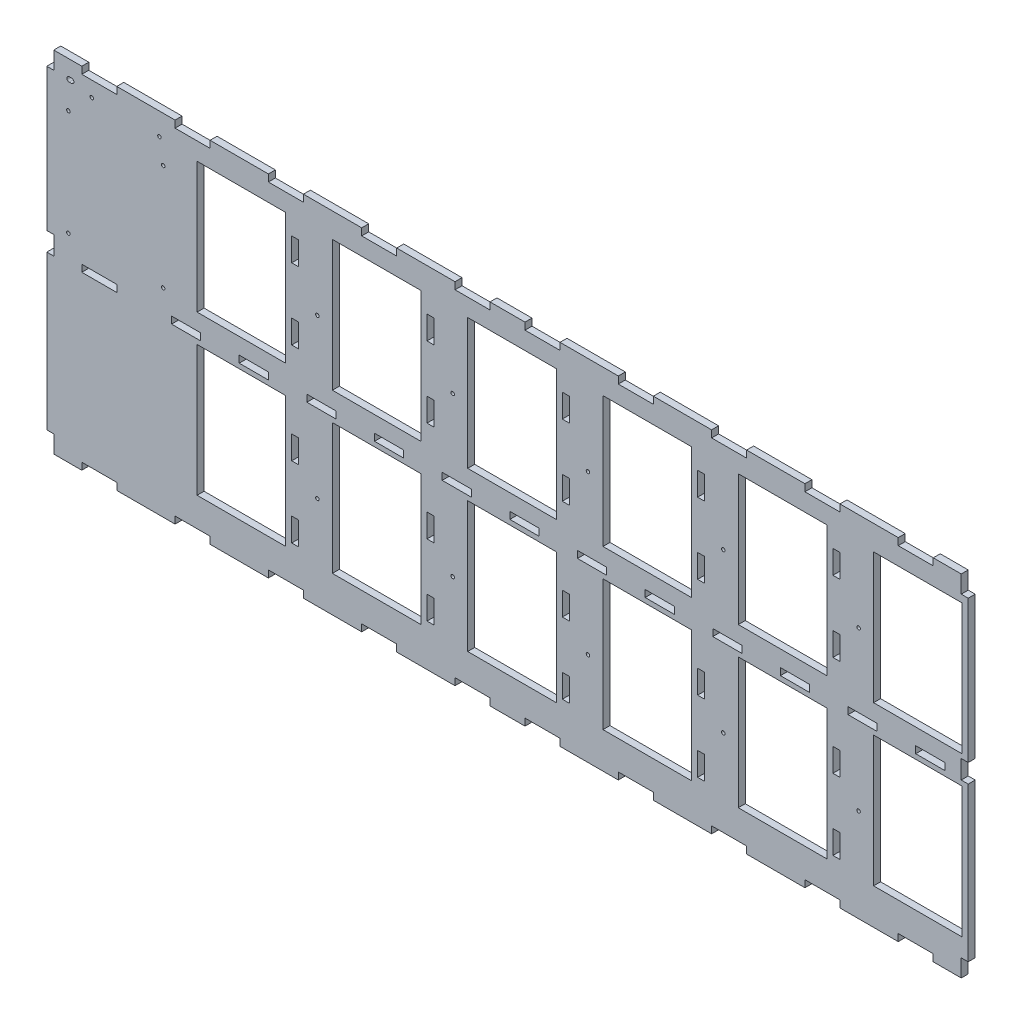
SolidWorks part; units mm, degrees
material "Acrylic (Medium-high impact)"
ref_plane "Front Plane" through (0, 0, 0) normal (0, 0, 1) x (1, 0, 0)
ref_plane "Top Plane" through (0, 0, 0) normal (0, 1, 0) x (1, 0, 0)
ref_plane "Right Plane" through (0, 0, 0) normal (1, 0, 0) x (0, 0, -1)
sketch "Sketch1" plane through (0, 0, 0) normal (0, 0, 1) x (1, 0, 0)
  line L1 (395, -150) -> (-395, -150)
  line L2 (395, -150) -> (395, 150)
  line L3 (395, 150) -> (-395, 150)
  line L4 (-395, -150) -> (-395, 150)
  line L5 (395, -150) -> (-395, 150) construction
  line L6 (395, 150) -> (-395, -150) construction
  line L7 (-266.15, 16.85) -> (-190.15, 16.85)
  line L8 (-266.15, 16.85) -> (-266.15, 128.85)
  line L9 (-266.15, 128.85) -> (-190.15, 128.85)
  line L10 (-190.15, 16.85) -> (-190.15, 128.85)
  line L11 (-264.15, 18.85) -> (-264.15, 126.85) construction
  line L12 (-192.15, 18.85) -> (-264.15, 18.85) construction
  line L13 (-192.15, 126.85) -> (-192.15, 18.85) construction
  line L14 (-264.15, 126.85) -> (-192.15, 126.85) construction
  line L15 (-150.15, 16.85) -> (-74.15, 16.85)
  line L16 (-150.15, 16.85) -> (-150.15, 128.85)
  line L17 (-150.15, 128.85) -> (-74.15, 128.85)
  line L18 (-74.15, 16.85) -> (-74.15, 128.85)
  line L19 (-34.15, 16.85) -> (41.85, 16.85)
  line L20 (-34.15, 16.85) -> (-34.15, 128.85)
  line L21 (-34.15, 128.85) -> (41.85, 128.85)
  line L22 (41.85, 16.85) -> (41.85, 128.85)
  line L23 (81.85, 16.85) -> (157.85, 16.85)
  line L24 (81.85, 16.85) -> (81.85, 128.85)
  line L25 (81.85, 128.85) -> (157.85, 128.85)
  line L26 (157.85, 16.85) -> (157.85, 128.85)
  line L27 (197.85, 16.85) -> (273.85, 16.85)
  line L28 (197.85, 16.85) -> (197.85, 128.85)
  line L29 (197.85, 128.85) -> (273.85, 128.85)
  line L30 (273.85, 16.85) -> (273.85, 128.85)
  line L31 (-150.15, -119.15) -> (-74.15, -119.15)
  line L32 (-150.15, -119.15) -> (-150.15, -7.15)
  line L33 (-150.15, -7.15) -> (-74.15, -7.15)
  line L34 (-74.15, -119.15) -> (-74.15, -7.15)
  line L35 (-34.15, -119.15) -> (41.85, -119.15)
  line L36 (-34.15, -119.15) -> (-34.15, -7.15)
  line L37 (-34.15, -7.15) -> (41.85, -7.15)
  line L38 (41.85, -119.15) -> (41.85, -7.15)
  line L39 (81.85, -119.15) -> (157.85, -119.15)
  line L40 (81.85, -119.15) -> (81.85, -7.15)
  line L41 (81.85, -7.15) -> (157.85, -7.15)
  line L42 (157.85, -119.15) -> (157.85, -7.15)
  line L43 (197.85, -119.15) -> (273.85, -119.15)
  line L44 (197.85, -119.15) -> (197.85, -7.15)
  line L45 (197.85, -7.15) -> (273.85, -7.15)
  line L46 (273.85, -119.15) -> (273.85, -7.15)
  line L47 (-266.15, -119.15) -> (-190.15, -119.15)
  line L48 (-266.15, -119.15) -> (-266.15, -7.15)
  line L49 (-266.15, -7.15) -> (-190.15, -7.15)
  line L50 (-190.15, -119.15) -> (-190.15, -7.15)
  line L51 (313.85, 16.85) -> (389.85, 16.85)
  line L52 (313.85, 16.85) -> (313.85, 128.85)
  line L53 (313.85, 128.85) -> (389.85, 128.85)
  line L54 (389.85, 16.85) -> (389.85, 128.85)
  line L55 (313.85, -119.15) -> (389.85, -119.15)
  line L56 (313.85, -119.15) -> (313.85, -7.15)
  line L57 (313.85, -7.15) -> (389.85, -7.15)
  line L58 (389.85, -119.15) -> (389.85, -7.15)
  point P0 (0, 0)
  dimension "D1" = 790
  dimension "D2" = 300
  dimension "D3" = 2
  dimension "D4" = 2
  dimension "D5" = 2
  dimension "D6" = 2
  dimension "D7" = 6
  dimension "D8" = 2
extrude "Boss-Extrude1" add sketch "Sketch1" along normal blind 6
sketch "Sketch2" plane through (0, 0, 6) normal (0, 0, 1) x (1, 0, 0)
  line L0 (336, -70) -> (301, -70) construction
  line L1 (336, 66) -> (301, 66) construction
  circle A0 centre (301, -70) radius 1.5
  circle A1 centre (301, 66) radius 1.5
  circle A2 centre (185, -70) radius 1.5
  circle A3 centre (185, 66) radius 1.5
  circle A4 centre (69, -70) radius 1.5
  circle A5 centre (69, 66) radius 1.5
  circle A6 centre (-47, -70) radius 1.5
  circle A7 centre (-47, 66) radius 1.5
  circle A8 centre (-163, -70) radius 1.5
  circle A9 centre (-163, 66) radius 1.5
  circle A10 centre (-295.18, 20.3188) radius 1.5
  circle A11 centre (-376.46, 20.3188) radius 1.5
  circle A12 centre (-376.46, 111.1612) radius 1.5
  circle A13 centre (-295.18, 111.1612) radius 1.5
  circle A14 centre (-298.4147, 130.9983) radius 1.5
  circle A15 centre (-356.4147, 130.9983) radius 1.5
  dimension "D2" = 3
  dimension "D1" = 35
  dimension "D3" = 5
extrude "Cut-Extrude1" cut sketch "Sketch2" against normal blind 10
sketch "Sketch3" plane through (0, 0, 6) normal (0, 0, 1) x (1, 0, 0)
  line L0 (395, -150) -> (395, 150) construction
  line L1 (395, 135) -> (389, 135)
  line L2 (395, 135) -> (395, 150)
  line L3 (395, 150) -> (389, 150)
  line L4 (389, 135) -> (389, 150)
  line L5 (395, 150) -> (-395, 150) construction
  line L6 (389, 150) -> (389, 135) construction
  line L7 (395, -3) -> (389, -3)
  line L8 (395, -3) -> (395, 13)
  line L9 (395, 13) -> (389, 13)
  line L10 (389, -3) -> (389, 13)
  line L11 (-395, -150) -> (395, -150) construction
  line L12 (395, -135) -> (389, -135)
  line L13 (395, -135) -> (395, -150)
  line L14 (395, -150) -> (389, -150)
  line L15 (389, -135) -> (389, -150)
  line L16 (0, 50.7716) -> (0, 0) construction
  line L18 (0, 0) -> (100.6607, 0) construction
  line L19 (-389, -135) -> (-389, -150)
  line L20 (-395, -150) -> (-389, -150)
  line L21 (-395, -135) -> (-395, -150)
  line L22 (-395, -135) -> (-389, -135)
  line L23 (-389, -3) -> (-389, 13)
  line L24 (-395, 13) -> (-389, 13)
  line L25 (-395, -3) -> (-395, 13)
  line L26 (-395, -3) -> (-389, -3)
  line L27 (-389, 135) -> (-389, 150)
  line L28 (-395, 150) -> (-389, 150)
  line L29 (-395, 135) -> (-395, 150)
  line L30 (-395, 135) -> (-389, 135)
  line L31 (15, 144) -> (15, 150) construction
  line L32 (45, 144) -> (15, 144) construction
  line L33 (45, 150) -> (45, 144) construction
  line L34 (15, 144) -> (15, 150)
  line L35 (45, 144) -> (15, 144)
  line L36 (45, 150) -> (45, 144)
  line L37 (45, 150) -> (15, 150)
  line L38 (95, 144) -> (95, 150)
  line L39 (125, 144) -> (95, 144)
  line L40 (125, 150) -> (125, 144)
  line L41 (125, 150) -> (95, 150)
  line L42 (175, 144) -> (175, 150)
  line L43 (205, 144) -> (175, 144)
  line L44 (205, 150) -> (205, 144)
  line L45 (205, 150) -> (175, 150)
  line L46 (255, 144) -> (255, 150)
  line L47 (285, 144) -> (255, 144)
  line L48 (285, 150) -> (285, 144)
  line L49 (285, 150) -> (255, 150)
  line L50 (335, 144) -> (335, 150)
  line L51 (365, 144) -> (335, 144)
  line L52 (365, 150) -> (365, 144)
  line L53 (365, 150) -> (335, 150)
  line L54 (-365, 150) -> (-335, 150)
  line L55 (-365, 150) -> (-365, 144)
  line L56 (-365, 144) -> (-335, 144)
  line L57 (-335, 144) -> (-335, 150)
  line L58 (-285, 150) -> (-255, 150)
  line L59 (-285, 150) -> (-285, 144)
  line L60 (-285, 144) -> (-255, 144)
  line L61 (-255, 144) -> (-255, 150)
  line L62 (-205, 150) -> (-175, 150)
  line L63 (-205, 150) -> (-205, 144)
  line L64 (-205, 144) -> (-175, 144)
  line L65 (-175, 144) -> (-175, 150)
  line L66 (-125, 150) -> (-95, 150)
  line L67 (-125, 150) -> (-125, 144)
  line L68 (-125, 144) -> (-95, 144)
  line L69 (-95, 144) -> (-95, 150)
  line L70 (-45, 150) -> (-15, 150)
  line L71 (-45, 150) -> (-45, 144)
  line L72 (-45, 144) -> (-15, 144)
  line L73 (-15, 144) -> (-15, 150)
  line L74 (-15, -144) -> (-15, -150)
  line L75 (-45, -144) -> (-15, -144)
  line L76 (-45, -150) -> (-45, -144)
  line L77 (-45, -150) -> (-15, -150)
  line L78 (-95, -144) -> (-95, -150)
  line L79 (-125, -144) -> (-95, -144)
  line L80 (-125, -150) -> (-125, -144)
  line L81 (-125, -150) -> (-95, -150)
  line L82 (-175, -144) -> (-175, -150)
  line L83 (-205, -144) -> (-175, -144)
  line L84 (-205, -150) -> (-205, -144)
  line L85 (-205, -150) -> (-175, -150)
  line L86 (-255, -144) -> (-255, -150)
  line L87 (-285, -144) -> (-255, -144)
  line L88 (-285, -150) -> (-285, -144)
  line L89 (-285, -150) -> (-255, -150)
  line L90 (-335, -144) -> (-335, -150)
  line L91 (-365, -144) -> (-335, -144)
  line L92 (-365, -150) -> (-365, -144)
  line L93 (-365, -150) -> (-335, -150)
  line L94 (365, -150) -> (335, -150)
  line L95 (365, -150) -> (365, -144)
  line L96 (365, -144) -> (335, -144)
  line L97 (335, -144) -> (335, -150)
  line L98 (285, -150) -> (255, -150)
  line L99 (285, -150) -> (285, -144)
  line L100 (285, -144) -> (255, -144)
  line L101 (255, -144) -> (255, -150)
  line L102 (205, -150) -> (175, -150)
  line L103 (205, -150) -> (205, -144)
  line L104 (205, -144) -> (175, -144)
  line L105 (175, -144) -> (175, -150)
  line L106 (125, -150) -> (95, -150)
  line L107 (125, -150) -> (125, -144)
  line L108 (125, -144) -> (95, -144)
  line L109 (95, -144) -> (95, -150)
  line L110 (45, -150) -> (15, -150)
  line L111 (45, -150) -> (45, -144)
  line L112 (45, -144) -> (15, -144)
  line L113 (15, -144) -> (15, -150)
  dimension "D1" = 15
  dimension "D2" = 15
  dimension "D3" = 122
  dimension "D4" = 132
  dimension "D5" = 5
extrude "Cut-Extrude2" cut sketch "Sketch3" against normal blind 6
sketch "Sketch4" plane through (0, 0, 6) normal (0, 0, 1) x (1, 0, 0)
  line L0 (317, -3) -> (317, 3)
  line L1 (317, 3) -> (292, 3)
  line L2 (292, 3) -> (292, -3)
  line L3 (292, -3) -> (317, -3)
  line L4 (279, -94) -> (279, -114)
  line L5 (279, -114) -> (285, -114)
  line L6 (285, -114) -> (285, -94)
  line L7 (285, -94) -> (279, -94)
  line L8 (279, -94) -> (279, -114)
  line L9 (279, -114) -> (285, -114)
  line L10 (285, -114) -> (285, -94)
  line L11 (285, -94) -> (279, -94)
  line L12 (279, -33) -> (279, -53)
  line L13 (279, -53) -> (285, -53)
  line L14 (285, -53) -> (285, -33)
  line L15 (285, -33) -> (279, -33)
  line L16 (279, -33) -> (279, -53)
  line L17 (279, -53) -> (285, -53)
  line L18 (285, -53) -> (285, -33)
  line L19 (285, -33) -> (279, -33)
  line L20 (279, 53) -> (279, 33)
  line L21 (279, 33) -> (285, 33)
  line L22 (285, 33) -> (285, 53)
  line L23 (285, 53) -> (279, 53)
  line L24 (279, 53) -> (279, 33)
  line L25 (279, 33) -> (285, 33)
  line L26 (285, 33) -> (285, 53)
  line L27 (285, 53) -> (279, 53)
  line L28 (279, 114) -> (279, 94)
  line L29 (279, 94) -> (285, 94)
  line L30 (285, 94) -> (285, 114)
  line L31 (285, 114) -> (279, 114)
  line L32 (279, 114) -> (279, 94)
  line L33 (279, 94) -> (285, 94)
  line L34 (285, 94) -> (285, 114)
  line L35 (285, 114) -> (279, 114)
  line L36 (375, -3) -> (375, 3)
  line L37 (375, 3) -> (350, 3)
  line L38 (350, 3) -> (350, -3)
  line L39 (350, -3) -> (375, -3)
  line L40 (375, -3) -> (375, 3)
  line L41 (375, 3) -> (350, 3)
  line L42 (350, 3) -> (350, -3)
  line L43 (350, -3) -> (375, -3)
  line L44 (259, -3) -> (259, 3)
  line L45 (259, 3) -> (234, 3)
  line L46 (234, 3) -> (234, -3)
  line L47 (234, -3) -> (259, -3)
  line L48 (201, -3) -> (201, 3)
  line L49 (201, 3) -> (176, 3)
  line L50 (176, 3) -> (176, -3)
  line L51 (176, -3) -> (201, -3)
  line L52 (143, -3) -> (143, 3)
  line L53 (143, 3) -> (118, 3)
  line L54 (118, 3) -> (118, -3)
  line L55 (118, -3) -> (143, -3)
  line L56 (85, -3) -> (85, 3)
  line L57 (85, 3) -> (60, 3)
  line L58 (60, 3) -> (60, -3)
  line L59 (60, -3) -> (85, -3)
  line L60 (27, -3) -> (27, 3)
  line L61 (27, 3) -> (2, 3)
  line L62 (2, 3) -> (2, -3)
  line L63 (2, -3) -> (27, -3)
  line L64 (-31, -3) -> (-31, 3)
  line L65 (-31, 3) -> (-56, 3)
  line L66 (-56, 3) -> (-56, -3)
  line L67 (-56, -3) -> (-31, -3)
  line L68 (-89, -3) -> (-89, 3)
  line L69 (-89, 3) -> (-114, 3)
  line L70 (-114, 3) -> (-114, -3)
  line L71 (-114, -3) -> (-89, -3)
  line L72 (-147, -3) -> (-147, 3)
  line L73 (-147, 3) -> (-172, 3)
  line L74 (-172, 3) -> (-172, -3)
  line L75 (-172, -3) -> (-147, -3)
  line L76 (-205, -3) -> (-205, 3)
  line L77 (-205, 3) -> (-230, 3)
  line L78 (-230, 3) -> (-230, -3)
  line L79 (-230, -3) -> (-205, -3)
  line L80 (-263, -3) -> (-263, 3)
  line L81 (-263, 3) -> (-288, 3)
  line L82 (-288, 3) -> (-288, -3)
  line L83 (-288, -3) -> (-263, -3)
  line L84 (163, -94) -> (163, -114)
  line L85 (163, -114) -> (169, -114)
  line L86 (169, -114) -> (169, -94)
  line L87 (169, -94) -> (163, -94)
  line L88 (163, -33) -> (163, -53)
  line L89 (163, -53) -> (169, -53)
  line L90 (169, -53) -> (169, -33)
  line L91 (169, -33) -> (163, -33)
  line L92 (163, 53) -> (163, 33)
  line L93 (163, 33) -> (169, 33)
  line L94 (169, 33) -> (169, 53)
  line L95 (169, 53) -> (163, 53)
  line L96 (163, 114) -> (163, 94)
  line L97 (163, 94) -> (169, 94)
  line L98 (169, 94) -> (169, 114)
  line L99 (169, 114) -> (163, 114)
  line L100 (47, -94) -> (47, -114)
  line L101 (47, -114) -> (53, -114)
  line L102 (53, -114) -> (53, -94)
  line L103 (53, -94) -> (47, -94)
  line L104 (47, -33) -> (47, -53)
  line L105 (47, -53) -> (53, -53)
  line L106 (53, -53) -> (53, -33)
  line L107 (53, -33) -> (47, -33)
  line L108 (47, 53) -> (47, 33)
  line L109 (47, 33) -> (53, 33)
  line L110 (53, 33) -> (53, 53)
  line L111 (53, 53) -> (47, 53)
  line L112 (47, 114) -> (47, 94)
  line L113 (47, 94) -> (53, 94)
  line L114 (53, 94) -> (53, 114)
  line L115 (53, 114) -> (47, 114)
  line L116 (-69, -94) -> (-69, -114)
  line L117 (-69, -114) -> (-63, -114)
  line L118 (-63, -114) -> (-63, -94)
  line L119 (-63, -94) -> (-69, -94)
  line L120 (-69, -33) -> (-69, -53)
  line L121 (-69, -53) -> (-63, -53)
  line L122 (-63, -53) -> (-63, -33)
  line L123 (-63, -33) -> (-69, -33)
  line L124 (-69, 53) -> (-69, 33)
  line L125 (-69, 33) -> (-63, 33)
  line L126 (-63, 33) -> (-63, 53)
  line L127 (-63, 53) -> (-69, 53)
  line L128 (-69, 114) -> (-69, 94)
  line L129 (-69, 94) -> (-63, 94)
  line L130 (-63, 94) -> (-63, 114)
  line L131 (-63, 114) -> (-69, 114)
  line L132 (-185, -94) -> (-185, -114)
  line L133 (-185, -114) -> (-179, -114)
  line L134 (-179, -114) -> (-179, -94)
  line L135 (-179, -94) -> (-185, -94)
  line L136 (-185, -33) -> (-185, -53)
  line L137 (-185, -53) -> (-179, -53)
  line L138 (-179, -53) -> (-179, -33)
  line L139 (-179, -33) -> (-185, -33)
  line L140 (-185, 53) -> (-185, 33)
  line L141 (-185, 33) -> (-179, 33)
  line L142 (-179, 33) -> (-179, 53)
  line L143 (-179, 53) -> (-185, 53)
  line L144 (-185, 114) -> (-185, 94)
  line L145 (-185, 94) -> (-179, 94)
  line L146 (-179, 94) -> (-179, 114)
  line L147 (-179, 114) -> (-185, 114)
  line L152 (-335, 3) -> (-365, 3)
  line L153 (-365, 3) -> (-365, -3)
  line L154 (-365, -3) -> (-335, -3)
  line L155 (-335, -3) -> (-335, 3)
  line L156 (-335, 3) -> (-365, 3)
  line L157 (-365, 3) -> (-365, -3)
  line L158 (-365, -3) -> (-335, -3)
  line L159 (-335, -3) -> (-335, 3)
  dimension "D1" = 0
  dimension "D2" = 0
  dimension "D3" = 0
  dimension "D4" = 0
  dimension "D5" = 0
  dimension "D8" = 0
  dimension "D6" = 12
  dimension "D7" = 5
extrude "Cut-Extrude3" cut sketch "Sketch4" against normal blind 6
sketch "Sketch5" plane through (0, 0, 6) normal (0, 0, 1) x (1, 0, 0)
  line L0 (-373.7855, 134.8185) -> (-375.7855, 134.8185) construction
  line L1 (-373.7855, 132.8185) -> (-375.7855, 132.8185)
  line L2 (-373.7855, 136.8185) -> (-375.7855, 136.8185)
  arc A0 (-373.7855, 132.8185) -> (-373.7855, 136.8185) centre (-373.7855, 134.8185) ccw
  arc A1 (-375.7855, 136.8185) -> (-375.7855, 132.8185) centre (-375.7855, 134.8185) ccw
  point P2 (-374.7855, 134.8185)
  dimension "D1" = 4
  dimension "D2" = 6
extrude "Cut-Extrude4" cut sketch "Sketch5" against normal blind 6
